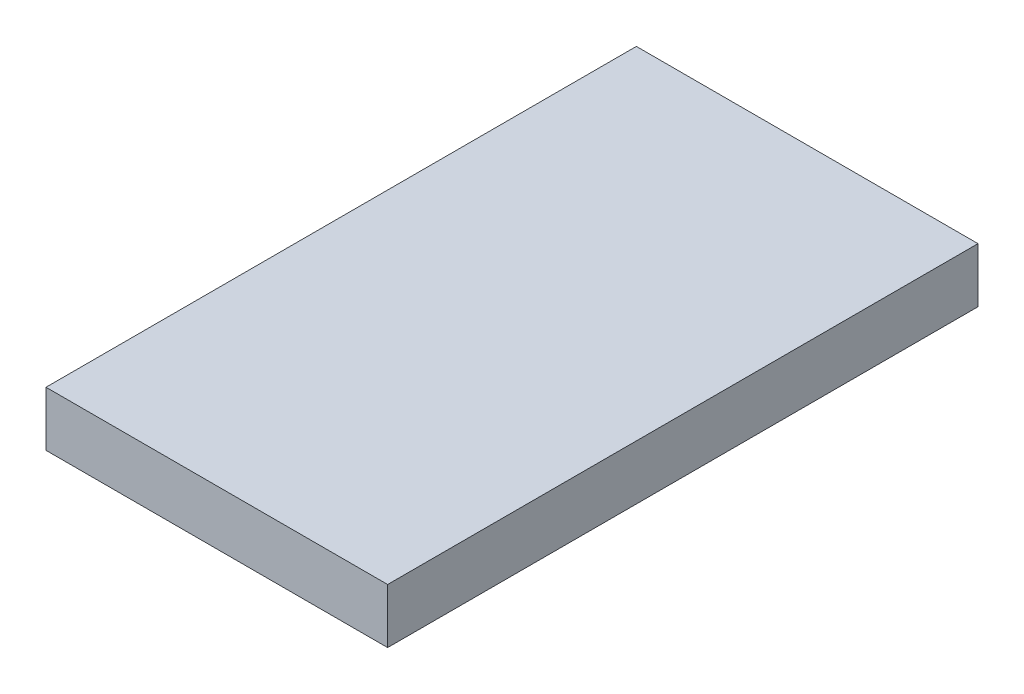
SolidWorks part; units mm, degrees
ref_plane "Front" through (0, 0, 0) normal (0, 0, 1) x (1, 0, 0)
ref_plane "Top" through (0, 0, 0) normal (0, 1, 0) x (1, 0, 0)
ref_plane "Right" through (0, 0, 0) normal (1, 0, 0) x (0, 0, -1)
sketch "Эскиз1" plane through (0, 0, 0) normal (0, 1, 0) x (1, 0, 0)
  line L0 (27.163, 67.2201) -> (147.4799, 67.2201) construction
  line L1 (0, 0) -> (25, 0)
  line L2 (12.2739, -21.4776) -> (12.8841, -21.4776)
  line L3 (12.8841, -21.4776) -> (12.8841, -16.4776)
  line L4 (12.8841, -16.4776) -> (16.6186, -16.4776)
  line L5 (16.6186, -16.4776) -> (16.6186, -12.422)
  line L6 (16.6186, -12.422) -> (9.2936, -12.422)
  line L7 (9.2936, -12.422) -> (9.2936, -10.2588)
  line L8 (9.2936, -10.2588) -> (16.6186, -10.2588)
  line L9 (16.6186, -10.2588) -> (16.6186, -6.1969)
  line L10 (16.6186, -6.1969) -> (9.2936, -6.1969)
  line L11 (9.2936, -6.1969) -> (9.2936, -7.1342)
  line L12 (9.2936, -7.1342) -> (15.7832, -7.1342)
  line L13 (15.7832, -7.1342) -> (15.7832, -9.2974)
  line L14 (15.7832, -9.2974) -> (8.4524, -9.2974)
  line L15 (8.4524, -9.2974) -> (8.4524, -13.3354)
  line L16 (8.4524, -13.3354) -> (15.7832, -13.3354)
  line L17 (15.7832, -13.3354) -> (15.7832, -15.5947)
  line L18 (15.7832, -15.5947) -> (9.2936, -15.5947)
  line L19 (9.2936, -15.5947) -> (9.2936, -16.4776)
  line L20 (9.2936, -16.4776) -> (12.2739, -16.4776)
  line L21 (12.2739, -16.4776) -> (12.2739, -21.4776)
  dimension "D1" = 25
  dimension "D2" = 5
sketch "Эскиз2" plane through (0, 0, 0) normal (0, 1, 0) x (1, 0, 0)
  line L1 (7.4524, -5.1969) -> (17.4524, -5.1969)
  line L2 (7.4524, -5.1969) -> (7.4524, -22.4776)
  line L3 (7.4524, -22.4776) -> (17.4524, -22.4776)
  line L4 (17.4524, -5.1969) -> (17.4524, -22.4776)
  line L5 (8.4524, -9.2974) -> (8.4524, -13.3354) construction
  line L7 (16.6186, -6.1969) -> (9.2936, -6.1969) construction
  dimension "D1" = 10
  dimension "D2" = 1
  dimension "D3" = 1
  dimension "D4" = 1
extrude "Бобышка-Вытянуть1" add sketch "Эскиз2" along normal blind 1.6
extrude "Бобышка-Вытянуть2" add sketch "Эскиз1" against normal blind 0.01 contours L17 L18 L19 L20 L21 L2 L3 L4 L5 L6 L7 L8 L9 L10 L11 L12 L13 L14 L15 L16
